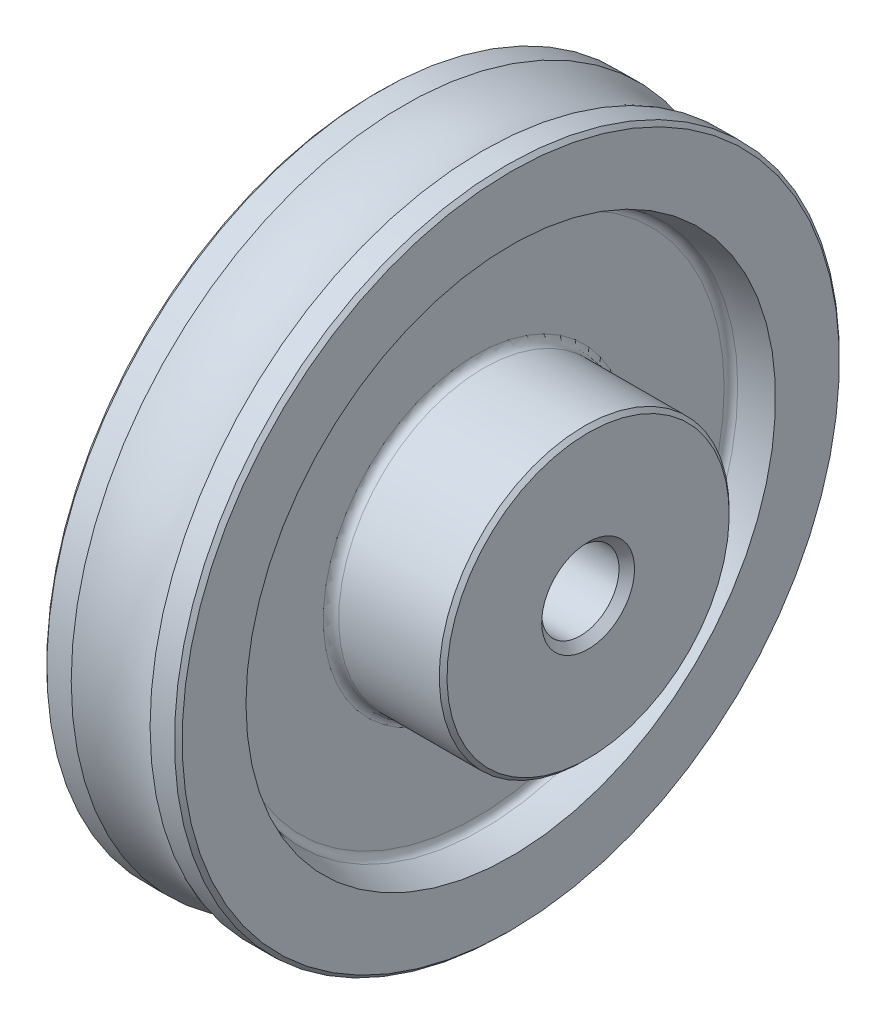
SolidWorks part; units mm, degrees
ref_plane "Alzado" through (0, 0, 0) normal (0, 0, 1) x (1, 0, 0)
ref_plane "Planta" through (0, 0, 0) normal (0, 1, 0) x (1, 0, 0)
ref_plane "Vista lateral" through (0, 0, 0) normal (1, 0, 0) x (0, 0, -1)
sketch "Croquis1" plane through (0, 0, 0) normal (0, 0, 1) x (1, 0, 0)
  line L0 (0, 0) -> (-17.5, 0) construction
  line L1 (-17.5, 0) -> (17.5, 0)
  line L2 (-17.5, 0) -> (-17.5, 86)
  line L3 (-17.5, 86) -> (17.5, 86)
  line L4 (17.5, 86) -> (17.5, 37.5)
  line L5 (17.5, 37.5) -> (37.5, 37.5)
  line L6 (37.5, 37.5) -> (37.5, 0)
  line L7 (37.5, 0) -> (17.5, 0)
  dimension "D1" = 17.5
  dimension "D2" = 20
  dimension "D3" = 86
  dimension "D4" = 55
  dimension "D5" = 37.5
revolve "Revolución1" add sketch "Croquis1" angle 360 about L0
sketch "Croquis2" plane through (0, 0, 0) normal (0, 0, 1) x (1, 0, 0)
  line L0 (0, 0) -> (-70.4514, 0) construction
  line L1 (0, 0) -> (0, 111) construction
  circle A0 centre (0, 111) radius 27
  point P3 (0, 84)
  dimension "D1" = 111
  dimension "D2" = 84
revolve "Cortar-Revolución1" cut sketch "Croquis2" angle 360 about L0
sketch "Croquis3" plane through (0, 0, 0) normal (0, 0, 1) x (1, 0, 0)
  line L0 (0, 0) -> (0, 111) construction
  line L1 (0, 0) -> (129.2288, 0) construction
  line L2 (-17.5, 86) -> (-17.5, -86) construction
  line L3 (-8.5, 37.5) -> (8.5, 37.5) construction
  line L4 (-8.5, 37.5) -> (-8.5, 65.8309)
  line L5 (-17.5, 68.5) -> (-17.5, 37.5)
  line L6 (-17.5, 37.5) -> (-8.5, 37.5)
  line L8 (8.5, 37.5) -> (8.5, 65.8309)
  line L9 (8.5, 37.5) -> (17.5, 37.5)
  line L10 (17.5, -37.5) -> (17.5, 37.5) construction
  line L11 (17.5, -86) -> (17.5, 86) construction
  line L12 (17.5, 37.5) -> (17.5, 68.5)
  circle A0 centre (0, 111) radius 31 construction
  arc A1 (-8.5, 65.8309) -> (-17.5, 68.5) centre (0, 111) cw
  arc A2 (17.5, 68.5) -> (8.5, 65.8309) centre (0, 111) cw
  point P3 (0, 80)
  dimension "D1" = 111
  dimension "D2" = 80
  dimension "D3" = 9
  dimension "D4" = 68.5
  dimension "D5" = 37.5
  dimension "D6" = 17
  dimension "D7" = 68.5
revolve "Cortar-Revolución2" cut sketch "Croquis3" angle 360 about L1
sketch "Croquis4" plane through (37.5, 0, 0) normal (1, 0, 0) x (0, 0, -1)
  circle A0 centre (0, 0) radius 10
  dimension "D1" = 20
extrude "Cortar-Extruir1" cut sketch "Croquis4" against normal through all
chamfer "Chaflán1" distance 1 angle 45 4 edges at (-17.5, 0, 37.5) (37.5, 37.5, 0) (17.5, 86, 0) (-17.5, 86, 0)
chamfer "Chaflán2" distance 2 angle 45 2 edges at (-17.5, 10, 0) (37.5, 10, 0)
fillet "Redondeo3" radius 2 2 edges at (8.5, 0, 65.8309) (-8.5, 0, 65.8309)
fillet "Redondeo5" radius 2 2 edges at (8.5, 0, 37.5) (-8.5, 0, 37.5)
